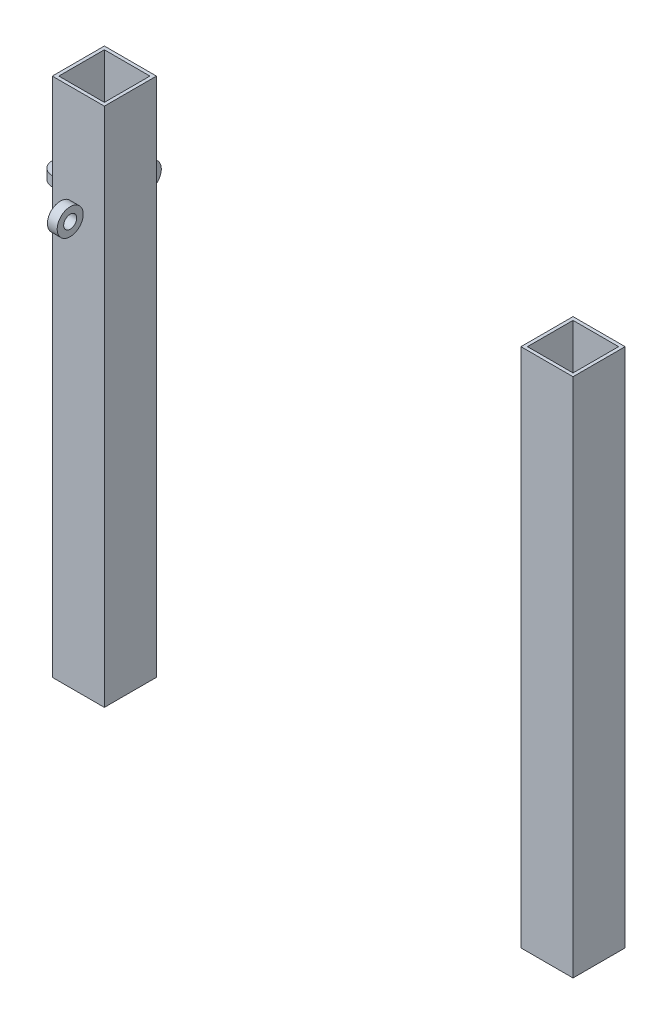
SolidWorks part; units mm, degrees
ref_plane "Front Plane" through (0, 0, 0) normal (0, 0, 1) x (1, 0, 0)
ref_plane "Top Plane" through (0, 0, 0) normal (0, 1, 0) x (1, 0, 0)
ref_plane "Right Plane" through (0, 0, 0) normal (1, 0, 0) x (0, 0, -1)
sketch "Sketch2" plane through (0, 0, 0) normal (0, 1, 0) x (1, 0, 0)
  line L0 (127, 70.2696) -> (127, -45.3231) construction
  line L1 (0, 0) -> (25.4, 0)
  line L2 (0, 0) -> (0, 25.4)
  line L3 (0, 25.4) -> (25.4, 25.4)
  line L4 (25.4, 0) -> (25.4, 25.4)
  line L5 (1.5875, 1.5875) -> (23.8125, 1.5875)
  line L6 (1.5875, 1.5875) -> (1.5875, 23.8125)
  line L7 (1.5875, 23.8125) -> (23.8125, 23.8125)
  line L8 (23.8125, 1.5875) -> (23.8125, 23.8125)
  line L9 (230.1875, 1.5875) -> (230.1875, 23.8125)
  line L10 (252.4125, 23.8125) -> (230.1875, 23.8125)
  line L11 (252.4125, 1.5875) -> (252.4125, 23.8125)
  line L16 (252.4125, 1.5875) -> (230.1875, 1.5875)
  line L17 (228.6, 0) -> (228.6, 25.4)
  line L18 (254, 25.4) -> (228.6, 25.4)
  line L19 (254, 0) -> (254, 25.4)
  line L20 (254, 0) -> (228.6, 0)
  dimension "D1" = 25.4
  dimension "D2" = 1.5875
  dimension "D3" = 1.5875
  dimension "D4" = 1.5875
  dimension "D5" = 1.5875
  dimension "D6" = 127
extrude "Boss-Extrude1" add sketch "Sketch2" along normal blind 254
sketch "Sketch4" plane through (0, 0, 0) normal (-1, 0, 0) x (0, 0, 1)
  line L0 (-25.4, 254) -> (-25.4, 0) construction
  line L1 (0, 254) -> (0, 0) construction
  line L3 (-25.4, 254) -> (0, 254) construction
  circle A2 centre (-31.75, 203.2) radius 6.35
  circle A3 centre (-31.75, 203.2) radius 3.175
  circle A4 centre (6.35, 203.2) radius 6.35
  circle A5 centre (6.35, 203.2) radius 3.175
  point P12 (0, 0)
  dimension "D1" = 6.35
  dimension "D2" = 12.7
  dimension "D3" = 50.8
extrude "Boss-Extrude2" add sketch "Sketch4" along normal blind 4.7625 from offset 15.0812 separate body offset against normal yes
sketch "Sketch5" plane through (0, 254, 0) normal (0, 1, 0) x (1, 0, 0)
  line L0 (0, 25.4) -> (0, 0) construction
  line L1 (25.4, 25.4) -> (0, 25.4) construction
  circle A0 centre (-6.35, 12.7) radius 6.35
  circle A1 centre (-6.35, 12.7) radius 3.175
  dimension "D1" = 12.7
  dimension "D2" = 6.35
  dimension "D3" = 12.7
extrude "Boss-Extrude3" add sketch "Sketch5" along normal blind 4.7625 from offset 53.1812 separate body offset against normal yes
